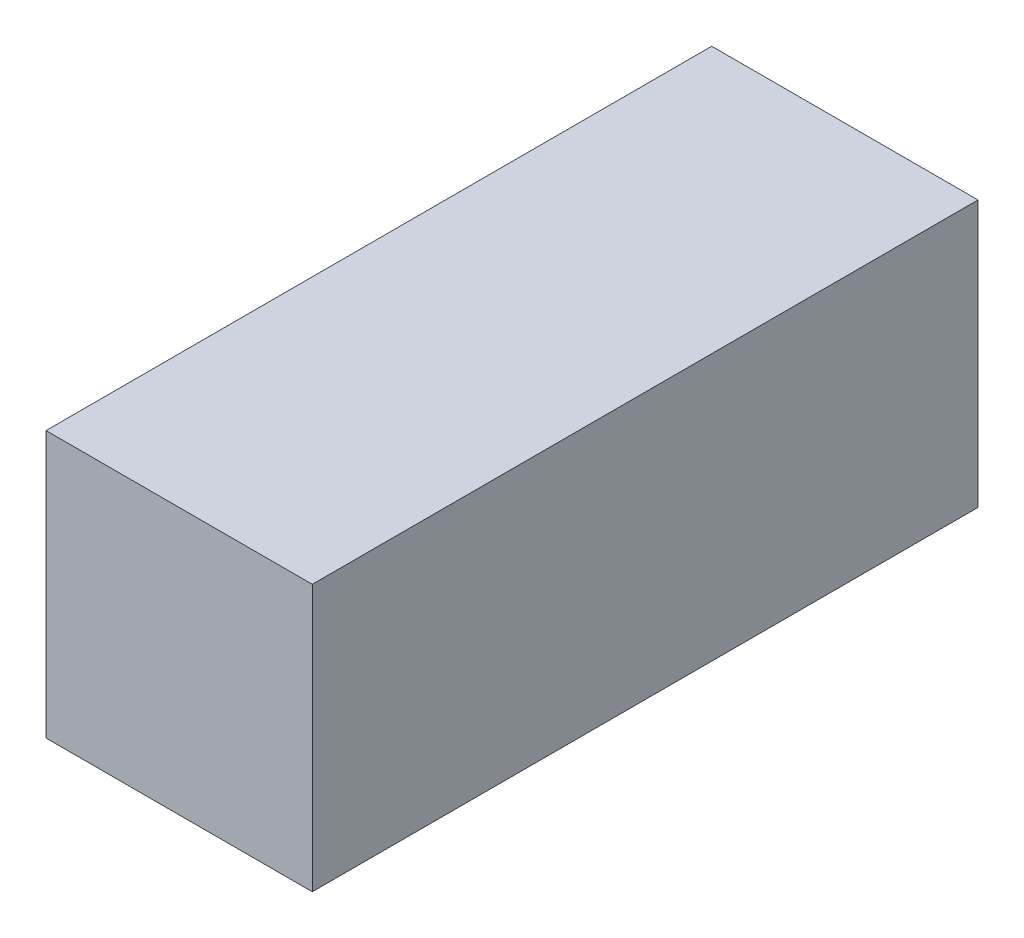
SolidWorks part; units mm, degrees
ref_plane "Front Plane" through (0, 0, 0) normal (0, 0, 1) x (1, 0, 0)
ref_plane "Top Plane" through (0, 0, 0) normal (0, 1, 0) x (1, 0, 0)
ref_plane "Right Plane" through (0, 0, 0) normal (1, 0, 0) x (0, 0, -1)
sketch "Sketch1" plane through (0, 0, 0) normal (0, 0, 1) x (1, 0, 0)
  line L1 (50.8, -50.8) -> (-50.8, -50.8)
  line L2 (50.8, -50.8) -> (50.8, 50.8)
  line L3 (50.8, 50.8) -> (-50.8, 50.8)
  line L4 (-50.8, -50.8) -> (-50.8, 50.8)
  line L5 (50.8, -50.8) -> (-50.8, 50.8) construction
  line L6 (50.8, 50.8) -> (-50.8, -50.8) construction
  point P0 (0, 0)
  dimension "D1" = 101.6
  dimension "D2" = 101.6
extrude "Boss-Extrude1" add sketch "Sketch1" along normal blind 254
